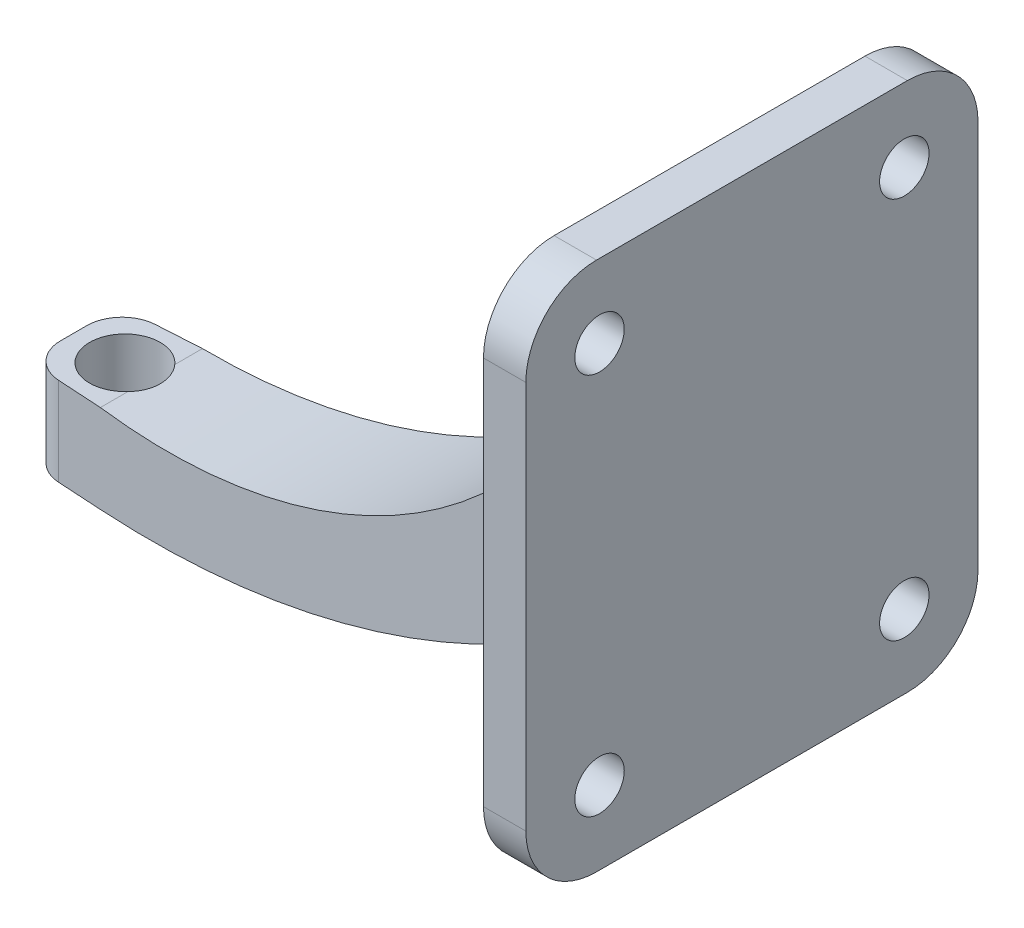
SolidWorks part; units mm, degrees
material "Galvanized Steel"
ref_plane "Front Plane" through (0, 0, 0) normal (0, 0, 1) x (1, 0, 0)
ref_plane "Top Plane" through (0, 0, 0) normal (0, 1, 0) x (1, 0, 0)
ref_plane "Right Plane" through (0, 0, 0) normal (1, 0, 0) x (0, 0, -1)
sketch "Sketch1" plane through (0, 0, 0) normal (0, 0, 1) x (1, 0, 0)
  line L0 (0, 0) -> (0, 25.0004)
  line L1 (0, 25.0004) -> (22, 25.0004)
  line L3 (22, 0) -> (0, 0)
  line L4 (0, 25.0004) -> (0, -234) construction
  line L5 (0, -234) -> (180, -234) construction
  line L6 (180, -234) -> (180, 130.9294) construction
  line L7 (180, 130.9294) -> (180, 56.0265)
  arc A0 (22, 25.0004) -> (180, 130.9294) centre (32.8248, 179.6527) ccw
  arc A1 (22, 0) -> (180, 56.0265) centre (22, 250.8008) ccw
  dimension "D1" = 22
  dimension "D2" = 180
  dimension "D3" = 22
extrude "Boss-Extrude1" add sketch "Sketch1" along normal blind 48
sketch "Sketch2" plane through (0, 0, 48) normal (0, 0, 1) x (1, 0, 0)
  line L0 (0, 0) -> (0, 7.5) construction
  line L1 (0, 25.0004) -> (0, 0) construction
  line L2 (0, 7.5) -> (4.5, 7.5) construction
  line L3 (4.5, 7.5) -> (4.5, 17.5)
  line L4 (4.5, 17.5) -> (18.5, 17.5)
  line L5 (18.5, 17.5) -> (18.5, 7.5)
  line L6 (4.5, 7.5) -> (18.5, 7.5)
  dimension "D1" = 14
  dimension "D2" = 10
  dimension "D3" = 4.5
ref_plane "Plane1" through (0, 0, 24) normal (0, 0, 1) x (1, 0, 0)
ref_plane "Plane2" through (80, 0, 0) normal (-1, 0, 0) x (0, 0, 1)
sketch "Sketch7" plane through (80, 0, 0) normal (-1, 0, 0) x (0, 0, 1)
  line L0 (24, 25.0004) -> (24, 60.0004) construction
  line L1 (48, 25.0004) -> (0, 25.0004) construction
  circle A0 centre (24, 60.0004) radius 35
  circle A1 centre (24, 60.0004) radius 38.5
sketch "Sketch9" plane through (0, 0, 48) normal (0, 0, 1) x (1, 0, 0)
  line L0 (180, 130.9294) -> (180, 160.9294)
  line L1 (180, 160.9294) -> (192, 160.9294)
  line L2 (192, 160.9294) -> (192, 10.9294)
  line L3 (192, 10.9294) -> (180, 10.9294)
  line L4 (180, 10.9294) -> (180, 51.3088)
  line L5 (180, 56.0265) -> (180, 130.9294) construction
  line L6 (180, 51.3088) -> (180, 130.9294)
extrude "Boss-Extrude4" add sketch "Sketch9" along normal blind 40 and the other way blind 88
fillet "Fillet2" radius 20 4 edges at (186, 160.9294, 88) (186, 10.9294, 88) (186, 10.9294, -40) (186, 160.9294, -40)
sketch "Sketch10" plane through (180, 0, 0) normal (-1, 0, 0) x (0, 0, 1)
  line L0 (-19.1421, 31.7872) -> (-19.1421, 140.0715) construction
  line L5 (-19.1421, 140.0715) -> (67.1421, 140.0715) construction
  line L6 (67.1421, 31.7872) -> (67.1421, 140.0715) construction
  line L7 (-19.1421, 31.7872) -> (67.1421, 31.7872) construction
  circle A2 centre (-19.1421, 140.0715) radius 7
  circle A3 centre (67.1421, 140.0715) radius 7
  circle A4 centre (67.1421, 31.7872) radius 7
  circle A5 centre (-19.1421, 31.7872) radius 7
  dimension "D1" = 108.2843
  dimension "D2" = 86.2843
extrude "Cut-Extrude3" cut sketch "Sketch10" against normal blind 40
sketch "Sketch11" plane through (0, 0, 0) normal (0, 1, 0) x (1, 0, 0)
  line L0 (180, 0) -> (9.3966, -10.313)
  line L1 (0, -48) -> (0, 0) construction
  line L2 (0, -24) -> (180, -24) construction
  line L3 (180, -48) -> (180, 0) construction
  line L4 (180, -48) -> (9.3966, -37.687)
  line L5 (0, -20.2948) -> (0, -27.7052)
  line L6 (180, 0) -> (0, 0)
  line L7 (0, 0) -> (0, -20.2948)
  line L8 (180, -48) -> (0, -48)
  line L9 (0, -48) -> (0, -27.7052)
  circle A0 centre (11, -24) radius 8
  arc A1 (9.3966, -37.687) -> (0, -27.7052) centre (10, -27.7052) cw
  arc A2 (9.3966, -10.313) -> (0, -20.2948) centre (10, -20.2948) ccw
  point P16 (0, -37.119)
  point P19 (0, -10.881)
  dimension "D1" = 10
extrude "Cut-Extrude4" cut sketch "Sketch11" along normal blind 180 contours A2 L0 L6 L7 | A1 L4 L8 L9
sketch "Sketch12" plane through (0, 25.0004, 0) normal (0, 1, 0) x (1, 0, 0)
  line L0 (0, -24) -> (14.5, -24) construction
  line L1 (0, -27.7052) -> (0, -20.2948) construction
  circle A0 centre (14.5, -24) radius 10
extrude "Cut-Extrude5" cut sketch "Sketch12" against normal blind 180
